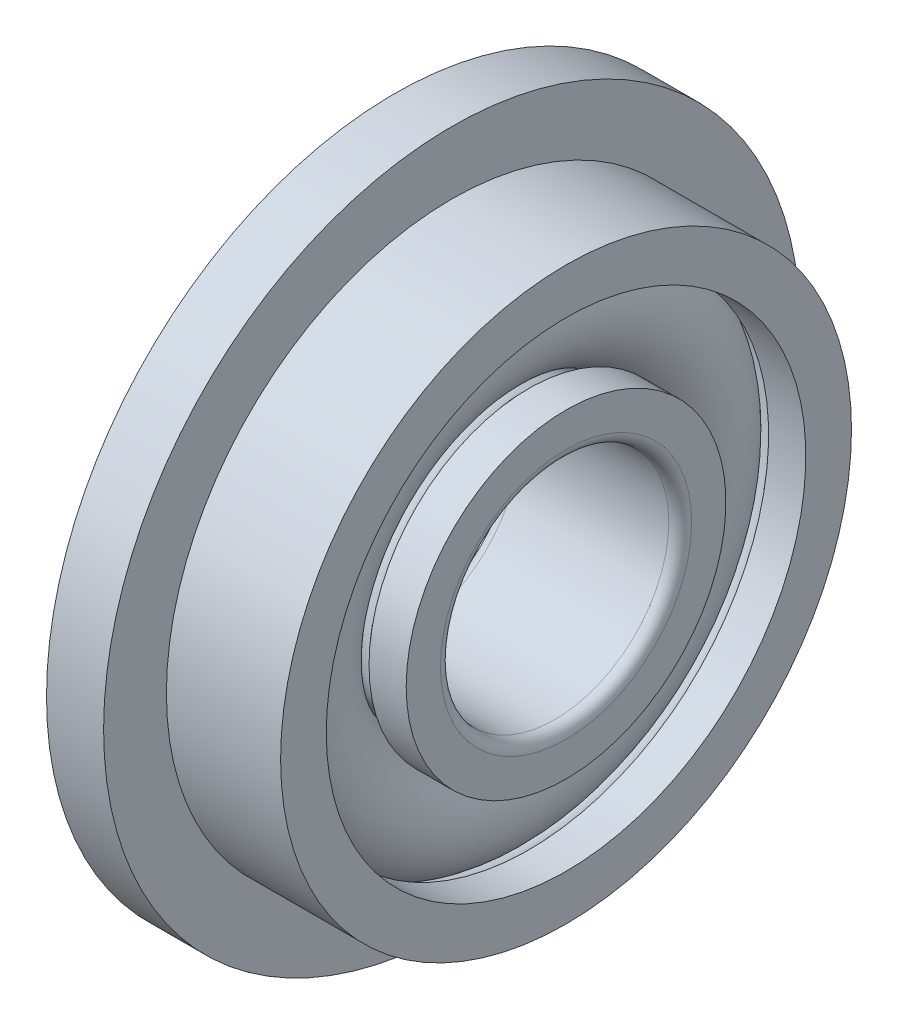
SolidWorks part; units mm, degrees
material "65Mn"
ref_plane "前视基准面" through (0, 0, 0) normal (0, 0, 1) x (1, 0, 0)
ref_plane "上视基准面" through (0, 0, 0) normal (0, 1, 0) x (1, 0, 0)
ref_plane "右视基准面" through (0, 0, 0) normal (1, 0, 0) x (0, 0, -1)
sketch "草图1" plane through (0, 0, 0) normal (0, 0, 1) x (1, 0, 0)
  line L0 (0, 0) -> (41.7577, 0) construction
  line L1 (0.5, 2.5) -> (1.5, 2.5)
  line L2 (0, 2.5) -> (0, 2.1)
  line L3 (0, 1) -> (1.5, 1)
  line L4 (1.5, 2.5) -> (1.5, 2.1)
  line L5 (0, 2.1) -> (0.3257, 2.1)
  line L6 (0, 1.4) -> (0.3257, 1.4)
  line L7 (1.5, 1.4) -> (1.5, 1)
  line L8 (0, 1.4) -> (0, 1)
  line L9 (1.1743, 2.1) -> (1.5, 2.1)
  line L10 (1.1743, 1.4) -> (1.5, 1.4)
  line L11 (0, 0) -> (0, 22.8798) construction
  line L12 (0, 2.5) -> (0, 3.05)
  line L13 (0, 3.05) -> (0.5, 3.05)
  line L14 (0.5, 3.05) -> (0.5, 2.5)
  circle A0 centre (0.75, 1.75) radius 0.5
  arc A1 (0.3257, 1.4) -> (1.1743, 1.4) centre (0.75, 1.75) ccw
  circle A2 centre (0.75, 1.75) radius 0.55 construction
  arc A3 (1.1743, 2.1) -> (0.3257, 2.1) centre (0.75, 1.75) ccw
  dimension "D4" = 5
  dimension "D6" = 1
  dimension "D7" = 0.55
  dimension "D10" = 0.55
  dimension "D3" = 2
  dimension "D8" = 0.4
  dimension "D2" = 0.75
  dimension "D1" = 1.5
  dimension "D5" = 0.75
  dimension "D9" = 0.4
  dimension "D11" = 0.5
revolve "旋转1" add sketch "草图1" angle 360 about L0
fillet "圆角2" radius 0.1 2 edges at (1.5, 0, 1) (0, 0, 1)
